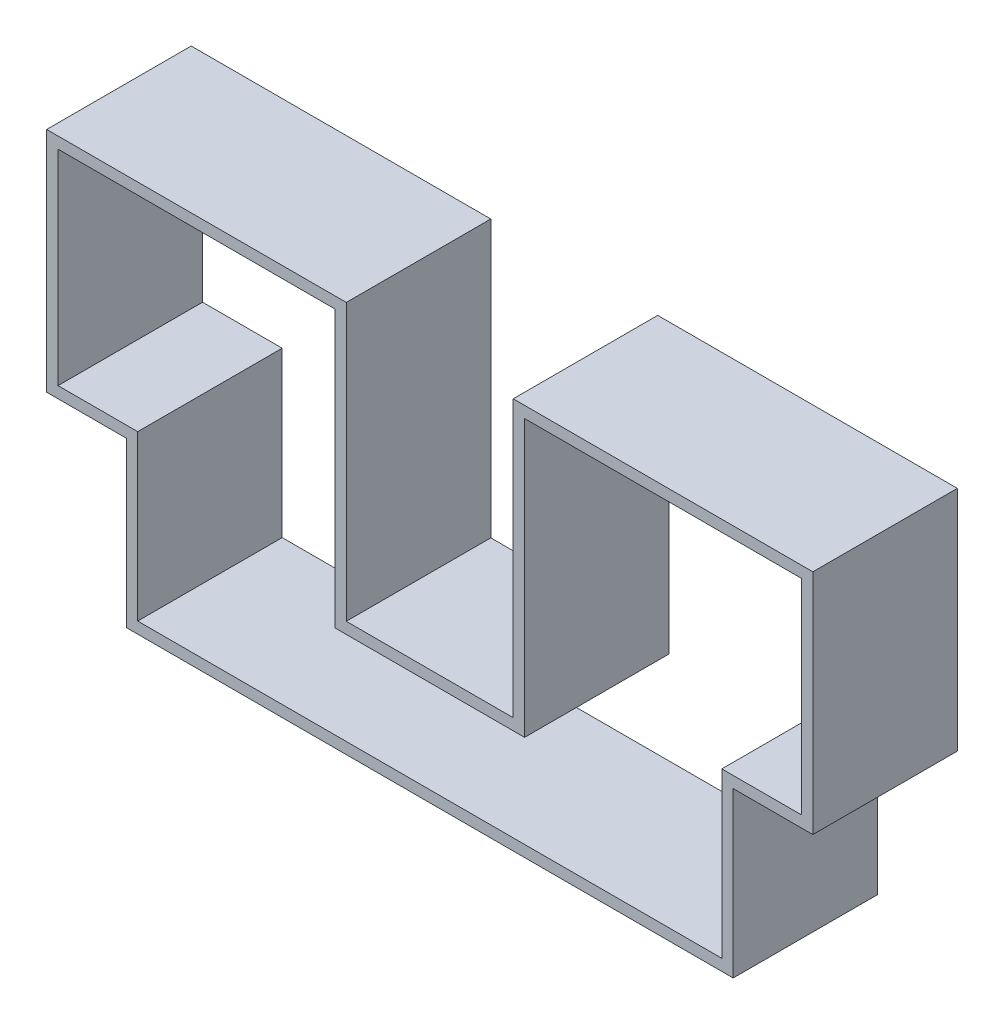
SolidWorks part; units mm, degrees
ref_plane "Front Plane" through (0, 0, 0) normal (0, 0, 1) x (1, 0, 0)
ref_plane "Top Plane" through (0, 0, 0) normal (0, 1, 0) x (1, 0, 0)
ref_plane "Right Plane" through (0, 0, 0) normal (1, 0, 0) x (0, 0, -1)
sketch "Sketch1" plane through (0, 0, 0) normal (0, 0, 1) x (1, 0, 0)
  line L0 (80, 0) -> (-80, 0)
  line L1 (-80, 0) -> (-80, 43.25)
  line L2 (-80, 43.25) -> (-101, 43.25)
  line L3 (-101, 43.25) -> (-101, 103.25)
  line L4 (-101, 103.25) -> (-22.006, 103.25)
  line L5 (-22.006, 103.25) -> (-22.006, 30.4415)
  line L6 (-22.006, 30.4415) -> (22.006, 30.4415)
  line L7 (0, 0) -> (0, 59.0292) construction
  line L8 (22.006, 103.25) -> (22.006, 30.4415)
  line L9 (101, 103.25) -> (22.006, 103.25)
  line L10 (101, 43.25) -> (101, 103.25)
  line L11 (80, 43.25) -> (101, 43.25)
  line L12 (80, 0) -> (80, 43.25)
  point P3 (0, 0)
  point P13 (0, 30.4415)
  dimension "D1" = 160
  dimension "D2" = 43.25
  dimension "D3" = 21
  dimension "D4" = 60
  dimension "D5" = 78.994
extrude "Boss-Extrude1" add sketch "Sketch1" along normal blind 38.1
shell "Shell2" thickness 3
